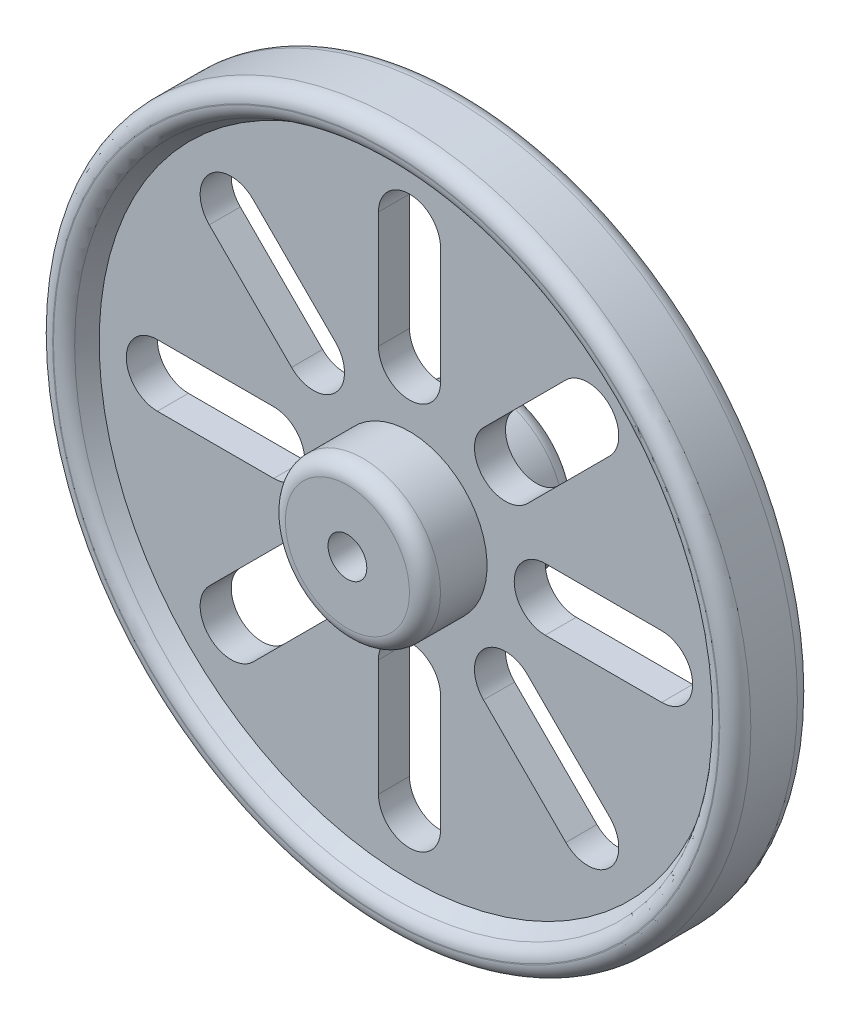
SolidWorks part; units mm, degrees
material "6061 Alloy"
ref_plane "Front Plane" through (0, 0, 0) normal (0, 0, 1) x (1, 0, 0)
ref_plane "Top Plane" through (0, 0, 0) normal (0, 1, 0) x (1, 0, 0)
ref_plane "Right Plane" through (0, 0, 0) normal (1, 0, 0) x (0, 0, -1)
sketch "Sketch1" plane through (0, 0, 0) normal (0, 0, 1) x (1, 0, 0)
  circle A0 centre (0, 0) radius 10
  dimension "D1" = 20
extrude "Boss-Extrude1" add sketch "Sketch1" along normal mid plane 20
sketch "Sketch2" plane through (0, 0, 0) normal (1, 0, 0) x (0, 0, -1)
  line L0 (0, 0) -> (0, 76.8354) construction
  line L1 (-5, 45) -> (5, 45)
  line L2 (5, 45) -> (5, 41.7321)
  line L3 (5, 41.7321) -> (2, 40)
  line L4 (2, 40) -> (2, 10)
  line L5 (10, 10) -> (-10, 10) construction
  line L6 (2, 10) -> (-2, 10)
  line L7 (-2, 40) -> (-2, 10)
  line L8 (-5, 41.7321) -> (-2, 40)
  line L9 (-5, 45) -> (-5, 41.7321)
  point P12 (0, 10)
  point P15 (0, 45)
  dimension "D1" = 30
  dimension "D2" = 35
  dimension "D3" = 10
  dimension "D4" = 30
  dimension "D5" = 4
revolve "Revolve1" add sketch "Sketch2" angle 360 about axis through (0, 0, 10) along (0, 0, -1)
sketch "Sketch3" plane through (0, 0, 2) normal (0, 0, 1) x (1, 0, 0)
  line L0 (0, 32.5) -> (0, 17.5) construction
  line L1 (4, 32.5) -> (4, 17.5)
  line L2 (-4, 32.5) -> (-4, 17.5)
  arc A0 (4, 32.5) -> (-4, 32.5) centre (0, 32.5) ccw
  arc A1 (-4, 17.5) -> (4, 17.5) centre (0, 17.5) ccw
  circle A2 centre (0, 0) radius 25 construction
  point P2 (0, 25)
  dimension "D2" = 4
  dimension "D3" = 50
  dimension "D1" = 15
extrude "Cut-Extrude1" cut sketch "Sketch3" against normal blind 10
pattern_circular "CirPattern1" count 8 over 360 about axis through (0, 0, 0) along (0, 0, 1) of "Cut-Extrude1"
fillet "Fillet1" radius 2 6 edges at (45, 0, 5) (41.7321, 0, 5) (10, 0, 10) (10, 0, -10) (41.7321, 0, -5) (45, 0, -5)
hole_wizard "Ø5.0 (5) Diameter Hole1" positions "Sketch5" profile "Sketch4" hole size "Ø5.0" standard "ANSI Metric" end condition through all
sketch "Sketch5" plane through (0, 0, 10) normal (0, 0, 1) x (1, 0, 0)
  point P0 (0, 0)
sketch "Sketch4" plane through (0, 0, 10) normal (1, 0, 0) x (0, -1, 0)
  line L0 (0, 0) -> (0, 20)
  line L1 (0, 20) -> (2.5, 20)
  line L2 (2.5, 20) -> (2.5, 0)
  line L5 (2.5, 0) -> (0, 0)
  line L11 (0, -6.35) -> (0, 107.95) construction
  dimension "Thru Hole Dia." = 5
  dimension "Thru Hole Depth" = 20
